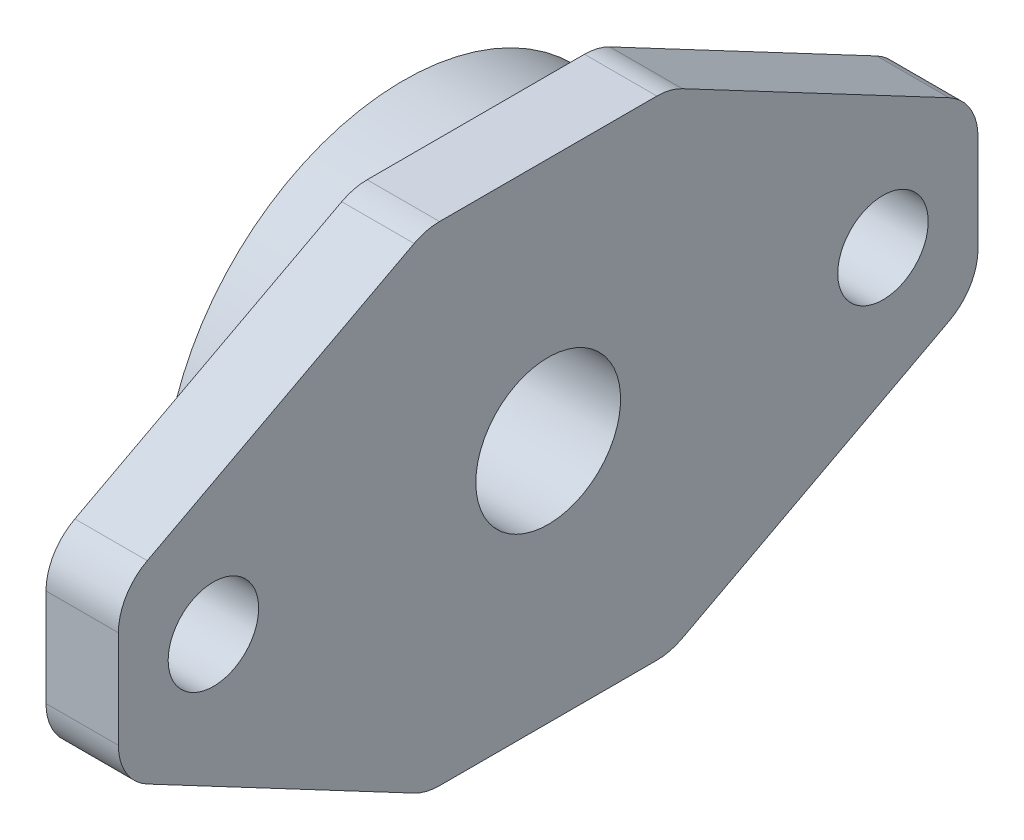
SolidWorks part; units mm, degrees
ref_plane "前视基准面" through (0, 0, 0) normal (0, 0, 1) x (1, 0, 0)
ref_plane "上视基准面" through (0, 0, 0) normal (0, 1, 0) x (1, 0, 0)
ref_plane "右视基准面" through (0, 0, 0) normal (1, 0, 0) x (0, 0, -1)
sketch "草图1" plane through (0, 0, 0) normal (1, 0, 0) x (0, 0, -1)
  line L1 (0, 0) -> (47.5, 0)
  line L2 (0, 0) -> (0, 27)
  line L3 (0, 27) -> (47.5, 27)
  line L4 (47.5, 0) -> (47.5, 27)
  dimension "D1" = 47.5
  dimension "D2" = 27
extrude "凸台-拉伸1" add sketch "草图1" along normal blind 4
sketch "草图5" plane through (0, 0, 0) normal (-1, 0, 0) x (0, 0, 1)
  line L0 (-47.5, 27) -> (0, 0) construction
  line L1 (0, 27) -> (-47.5, 0) construction
  circle A0 centre (-23.75, 13.5) radius 13.25
  dimension "D1" = 26.5
extrude "凸台-拉伸2" add sketch "草图5" along normal blind 4 contours A0
sketch "草图6" plane through (-4, 0, 0) normal (-1, 0, 0) x (0, 0, 1)
  circle A0 centre (-23.75, 13.5) radius 6
  dimension "D1" = 12
extrude "凸台-拉伸3" add sketch "草图6" along normal blind 3.5
sketch "草图7" plane through (-7.5, 0, 0) normal (-1, 0, 0) x (0, 0, 1)
  line L0 (-29.75, 13.5) -> (-17.75, 13.5) construction
  circle A0 centre (-23.75, 13.5) radius 6 construction
  circle A1 centre (-23.75, 13.5) radius 4
extrude "切除-拉伸1" cut sketch "草图7" against normal through all
sketch "草图8" plane through (0, 0, 0) normal (-1, 0, 0) x (0, 0, 1)
  line L0 (-47.5, 13.5) -> (0, 13.5) construction
  line L1 (-47.5, 0) -> (-47.5, 27) construction
  line L2 (0, 27) -> (0, 0) construction
  circle A0 centre (-42.25, 13.5) radius 2.5
  circle A1 centre (-5.25, 13.5) radius 2.5
  point P10 (-23.75, 13.5)
  dimension "D1" = 18.5
  dimension "D2" = 18.5
extrude "切除-拉伸2" cut sketch "草图8" against normal through all
sketch "草图9" plane through (0, 0, 0) normal (-1, 0, 0) x (0, 0, 1)
  line L0 (-47.5, 9) -> (-30.5, 0)
  line L1 (-47.5, 0) -> (-47.5, 27) construction
  line L2 (0, 0) -> (-47.5, 0) construction
  line L3 (-30.5, 0) -> (-47.5, 0)
  line L4 (-47.5, 0) -> (-47.5, 9)
  line L5 (-47.5, 18) -> (-30.5, 27)
  line L6 (-47.5, 27) -> (0, 27) construction
  line L7 (-30.5, 27) -> (-47.5, 27)
  line L8 (-47.5, 27) -> (-47.5, 18)
  line L9 (0, 0) -> (-17, 0)
  line L10 (-17, 0) -> (0, 9)
  line L11 (0, 27) -> (0, 0) construction
  line L12 (0, 9) -> (0, 0)
  line L13 (0, 18) -> (0, 27)
  line L14 (0, 27) -> (-17, 27)
  line L15 (-17, 27) -> (0, 18)
  dimension "D1" = 9
  dimension "D2" = 9
  dimension "D3" = 17
  dimension "D4" = 17
extrude "切除-拉伸3" cut sketch "草图9" against normal through all
fillet "圆角1" radius 3 8 edges at (2, 18, 0) (2, 9, 0) (2, 27, -30.5) (2, 27, -17) (2, 0, -17) (2, 0, -30.5) (2, 9, -47.5) (2, 18, -47.5)
